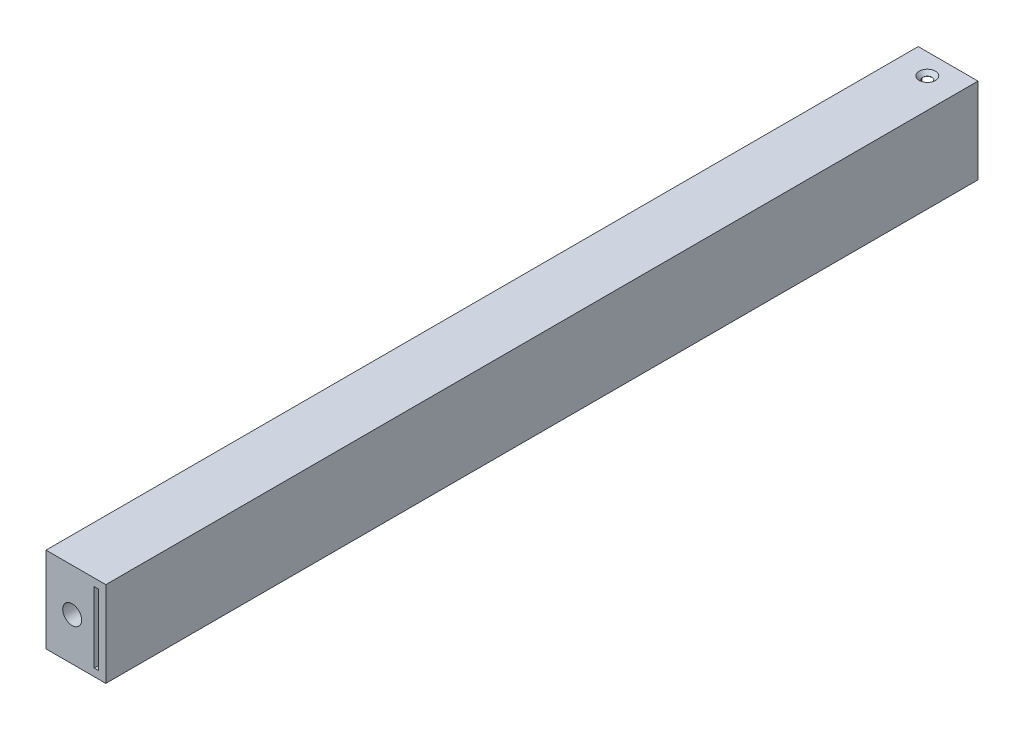
SolidWorks part; units mm, degrees
material "PET"
ref_plane "Front Plane" through (0, 0, 0) normal (0, 0, 1) x (1, 0, 0)
ref_plane "Top Plane" through (0, 0, 0) normal (0, 1, 0) x (1, 0, 0)
ref_plane "Right Plane" through (0, 0, 0) normal (1, 0, 0) x (0, 0, -1)
sketch "Sketch2" plane through (0, 0, 0) normal (0, 0, 1) x (1, 0, 0)
  line L12 (-6.3, 10.3) -> (-6.3, -10.3)
  line L13 (-6.3, -10.3) -> (8.1, -10.3)
  line L14 (8.1, -10.3) -> (8.1, 10.3)
  line L15 (8.1, 10.3) -> (-6.3, 10.3)
  line L16 (-6.3, 10.3) -> (-6.3, -10.3)
  line L17 (-6.3, -10.3) -> (8.1, -10.3)
  line L18 (8.1, -10.3) -> (8.1, 10.3)
  line L19 (8.1, 10.3) -> (-6.3, 10.3)
  line L20 (4.5, -8.5) -> (5.3, -8.5)
  line L21 (4.5, 8.5) -> (4.5, -8.5)
  line L22 (5.3, 8.5) -> (4.5, 8.5)
  line L23 (5.3, -8.5) -> (5.3, 8.5)
  line L25 (4.5, 8.5) -> (4.5, -8.5) construction
  line L27 (5.3, -8.5) -> (5.3, 8.5)
  line L28 (7.2, 9.4) -> (-5.4, 9.4)
  line L29 (7.2, -9.4) -> (7.2, 9.4)
  line L30 (-5.4, -9.4) -> (7.2, -9.4)
  line L31 (-5.4, 9.4) -> (-5.4, -9.4)
  line L32 (7.2, 9.4) -> (-5.4, 9.4) construction
  line L33 (7.2, -9.4) -> (7.2, 9.4) construction
  line L34 (-5.4, -9.4) -> (7.2, -9.4) construction
  line L35 (-5.4, 9.4) -> (-5.4, -9.4) construction
  line L36 (-4.5, -8.5) -> (6.3, -8.5)
  line L37 (6.3, -8.5) -> (6.3, 8.5)
  line L38 (6.3, 8.5) -> (-4.5, 8.5)
  line L39 (-4.5, 8.5) -> (-4.5, -8.5)
  line L40 (-4.5, -8.5) -> (6.3, -8.5) construction
  line L41 (6.3, -8.5) -> (6.3, 8.5)
  line L42 (6.3, 8.5) -> (-4.5, 8.5) construction
  line L43 (-4.5, 8.5) -> (-4.5, -8.5) construction
  line L48 (5.3, 8.5) -> (6.3, 8.5)
  line L49 (5.3, -8.5) -> (6.3, -8.5)
  circle A1 centre (0, 0) radius 4.7
  circle A2 centre (0, 0) radius 4.7 construction
  circle A3 centre (0, 0) radius 4.4
  circle A4 centre (0, 0) radius 4.4 construction
  dimension "D2" = 0
  dimension "D3" = 0
  dimension "D4" = 0
  dimension "D5" = 0
  dimension "D6" = 0
  dimension "D7" = 0
extrude "Top" add sketch "Sketch2" against normal blind 3.2
sketch "Sketch3" plane through (0, 0, -3.2) normal (0, 0, -1) x (-1, 0, 0)
  line L0 (4.5, 8.5) -> (4.5, -8.5) construction
  line L1 (4.5, 8.5) -> (4.5, -8.5)
  line L2 (-6.3, 8.5) -> (4.5, 8.5) construction
  line L3 (-6.3, 8.5) -> (4.5, 8.5)
  line L4 (6.3, 10.3) -> (-8.1, 10.3)
  line L5 (-8.1, 10.3) -> (-8.1, -10.3)
  line L6 (-8.1, -10.3) -> (6.3, -10.3)
  line L7 (6.3, -10.3) -> (6.3, 10.3)
  line L8 (6.3, 10.3) -> (-8.1, 10.3)
  line L9 (-8.1, 10.3) -> (-8.1, -10.3)
  line L10 (-8.1, -10.3) -> (6.3, -10.3)
  line L11 (6.3, -10.3) -> (6.3, 10.3)
  line L12 (-6.3, -8.5) -> (-6.3, 8.5) construction
  line L13 (-6.3, -8.5) -> (-6.3, 8.5)
  line L14 (4.5, -8.5) -> (-6.3, -8.5) construction
  line L15 (4.5, -8.5) -> (-6.3, -8.5)
  dimension "D1" = 0
extrude "Body" add sketch "Sketch3" along normal blind 196.8
sketch "Sketch4" plane through (0, 0, -200) normal (0, 0, -1) x (-1, 0, 0)
  line L0 (-7.21, 9.41) -> (5.41, 9.41)
  line L1 (5.41, 9.41) -> (5.41, -9.41)
  line L2 (5.41, -9.41) -> (-7.21, -9.41)
  line L3 (-7.21, -9.41) -> (-7.21, 9.41)
  line L4 (6.3, -10.3) -> (6.3, 10.3)
  line L5 (6.3, 10.3) -> (-8.1, 10.3)
  line L6 (-8.1, 10.3) -> (-8.1, -10.3)
  line L7 (-8.1, -10.3) -> (6.3, -10.3)
  line L8 (6.3, -10.3) -> (6.3, 10.3)
  line L9 (6.3, 10.3) -> (-8.1, 10.3)
  line L10 (-8.1, 10.3) -> (-8.1, -10.3)
  line L11 (-8.1, -10.3) -> (6.3, -10.3)
  line L12 (5.4, 9.4) -> (5.41, 9.4) construction
  line L14 (5.4, 9.4) -> (5.4, 9.41) construction
  line L16 (-7.2, -9.4) -> (-7.2, -9.41) construction
  line L18 (-7.2, -9.4) -> (-7.21, -9.4) construction
  dimension "D2" = 0.01
  dimension "D1" = 0
extrude "Insert" add sketch "Sketch4" along normal blind 10
sketch "Sketch5" plane through (0, 0, -3.2) normal (0, 0, -1) x (-1, 0, 0)
  line L0 (-4.5, 8.5) -> (-4.5, -8.5) construction
  line L1 (-4.5, 8.5) -> (-4.5, -8.5)
  line L2 (-5.3, -8.5) -> (-5.3, 8.5) construction
  line L3 (-5.3, -8.5) -> (-5.3, 8.5)
  line L4 (-5.3, 8.5) -> (-4.5, 8.5)
  line L5 (-5.3, -8.5) -> (-4.5, -8.5)
extrude "Flex" add sketch "Sketch5" along normal up to surface (196.8 mm away) up to face at (0.9, 0, -200)
sketch "Sketch6" plane through (0, 0, -3.2) normal (0, 0, -1) x (-1, 0, 0)
  circle A0 centre (0, 0) radius 4.7 construction
  circle A1 centre (0, 0) radius 4.7
  circle A2 centre (0, 0) radius 4.4 construction
  circle A3 centre (0, 0) radius 4.4
extrude "Lead screw" [suppressed] add sketch "Sketch6" along normal up to surface (60 mm away)
sketch "Sketch7" plane through (0, 0, -200) normal (0, 0, -1) x (-1, 0, 0)
  line L0 (4.5, 8.5) -> (4.5, -8.5) construction
  line L1 (4.5, 8.5) -> (4.5, -8.5) construction
  line L2 (4.4, 1.6523) -> (4.4, -1.6523)
  circle A0 centre (0, 0) radius 4.7 construction
  arc A1 (4.4, 1.6523) -> (4.4, -1.6523) centre (0, 0) ccw
  circle A2 centre (0, 0) radius 4.4 construction
  circle A3 centre (0, 0) radius 4.4
  dimension "D1" = 0.1
extrude "Insert lead screw" [suppressed] add sketch "Sketch7" along normal up to surface (10 mm away)
sketch "Sketch8" [suppressed] plane through (0, 0, 0) normal (0, 0, 1) x (1, 0, 0)
  circle A0 centre (0.9, 0) radius 1.35 construction
  circle A1 centre (0.9, 0) radius 1.35
  circle A2 centre (0.9, -6.45) radius 0.6 construction
  circle A3 centre (0.9, -6.45) radius 0.6 construction
  circle A4 centre (0.9, 6.45) radius 0.6 construction
  circle A5 centre (0.9, 6.45) radius 0.6 construction
  circle A6 centre (0.9, -6.45) radius 1.1
  circle A7 centre (0.9, 6.45) radius 1.1
  dimension "D1" = 2.2
extrude "Servo holes" [suppressed] cut sketch "Sketch8" against normal up to next
sketch "Sketch9" plane through (0, 0, 0) normal (0, 0, 1) x (1, 0, 0)
  circle A0 centre (0, 0) radius 2.275
  dimension "D1" = 4.55
extrude "Servo gear" cut sketch "Sketch9" against normal up to next
sketch "Join screw" plane through (0, -10.3, 0) normal (0, -1, 0) x (1, 0, 0)
  line L0 (0.9, -200) -> (0.9, -210) construction
  line L4 (7.21, -200) -> (-5.41, -200)
  line L5 (7.21, -210) -> (7.21, -200)
  line L6 (-5.41, -210) -> (7.21, -210)
  line L7 (-5.41, -200) -> (-5.41, -210)
  line L8 (7.21, -200) -> (-5.41, -200) construction
  line L9 (7.21, -210) -> (7.21, -200) construction
  line L10 (-5.41, -210) -> (7.21, -210) construction
  line L11 (-5.41, -200) -> (-5.41, -210) construction
  point P6 (0.9, -205)
  dimension "D1" = 0
hole_wizard "CSK for M2 Flat Head Machine Screw2" positions "Sketch14" profile "Sketch15" countersink size "M2" standard "ANSI Metric" end condition up to next
sketch "Sketch14" plane through (0, -10.3, 0) normal (0, -1, 0) x (-1, 0, 0)
  point P0 (-0.9, 205)
sketch "Sketch15" plane through (0.9, -10.3, -205) normal (1, 0, 0) x (0, 0, -1)
  line L0 (0, 0) -> (0, 0.89)
  line L1 (0, 0.89) -> (1.1, 0.89)
  line L2 (1.1, 0.89) -> (1.1, 0.85)
  line L3 (1.1, 0.85) -> (1.95, 0)
  line L5 (1.95, 0) -> (0, 0)
  line L6 (-1.1, 0.85) -> (-1.95, 0) construction
  line L11 (0, -6.35) -> (0, 107.95) construction
  dimension "Thru Hole Dia." = 2.2
  dimension "Thru Hole Depth" = 0.89
  dimension "Near C'Sink Dia." = 3.9
  dimension "Near C'Sink Angle" = 90
sketch "Sketch16" plane through (0, 10.3, 0) normal (0, 1, 0) x (1, 0, 0)
  point P0 (0.9, 205)
hole_wizard "CSK for M2 Flat Head Machine Screw3" positions "Sketch17" profile "Sketch18" countersink size "M2" standard "ANSI Metric" end condition up to next
sketch "Sketch17" plane through (0, 10.3, 0) normal (0, 1, 0) x (1, 0, 0)
  point P0 (0.9, 205)
sketch "Sketch18" plane through (0.9, 10.3, -205) normal (1, 0, 0) x (0, 0, 1)
  line L0 (0, 0) -> (0, 0.89)
  line L1 (0, 0.89) -> (1.1, 0.89)
  line L2 (1.1, 0.89) -> (1.1, 0.85)
  line L3 (1.1, 0.85) -> (1.95, 0)
  line L5 (1.95, 0) -> (0, 0)
  line L6 (-1.1, 0.85) -> (-1.95, 0) construction
  line L11 (0, -6.35) -> (0, 107.95) construction
  dimension "Thru Hole Dia." = 2.2
  dimension "Thru Hole Depth" = 0.89
  dimension "Near C'Sink Dia." = 3.9
  dimension "Near C'Sink Angle" = 90
chamfer "Chamfer1" distance 4 angle 45 4 edges at (-4.5, -8.5, -101.6) (-4.5, 8.5, -101.6) (4.5, 8.5, -101.6) (4.5, -8.5, -101.6)
